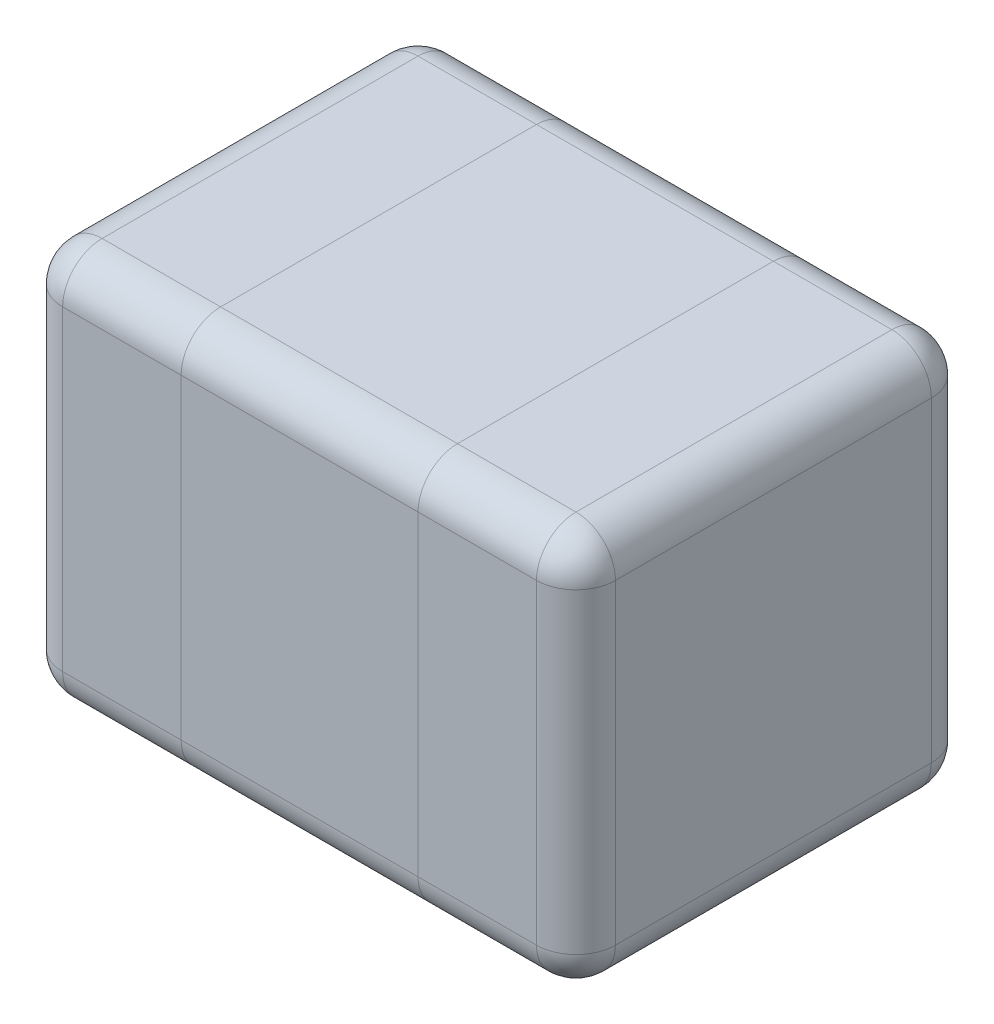
SolidWorks part; units mm, degrees
ref_plane "Alzado" through (0, 0, 0) normal (0, 0, 1) x (1, 0, 0)
ref_plane "Planta" through (0, 0, 0) normal (0, 1, 0) x (1, 0, 0)
ref_plane "Vista lateral" through (0, 0, 0) normal (1, 0, 0) x (0, 0, -1)
sketch "Croquis1" plane through (0, 0, 0) normal (0, 1, 0) x (1, 0, 0)
  line L1 (-0.15, -0.25) -> (0.15, -0.25)
  line L2 (-0.15, -0.25) -> (-0.15, 0.25)
  line L3 (-0.15, 0.25) -> (0.15, 0.25)
  line L4 (0.15, -0.25) -> (0.15, 0.25)
  line L5 (-0.15, -0.25) -> (0.15, 0.25) construction
  line L6 (-0.15, 0.25) -> (0.15, -0.25) construction
  point P0 (0, 0)
  dimension "D1" = 0.3
  dimension "D2" = 0.5
extrude "Saliente-Extruir1" add sketch "Croquis1" along normal blind 0.5
sketch "Croquis3" plane through (0, 0, 0) normal (0, 1, 0) x (1, 0, 0)
  line L0 (0.15, 0.25) -> (0.35, 0.25)
  line L1 (0.35, 0.25) -> (0.35, -0.25)
  line L2 (0.35, -0.25) -> (0.15, -0.25)
  line L3 (0.15, -0.25) -> (0.15, 0.25) construction
  line L4 (0.15, -0.25) -> (0.15, 0.25)
  line L5 (0, 1.3421) -> (0, -1.4057) construction
  line L6 (-0.15, -0.25) -> (-0.15, 0.25)
  line L7 (-0.35, -0.25) -> (-0.15, -0.25)
  line L8 (-0.35, 0.25) -> (-0.35, -0.25)
  line L9 (-0.15, 0.25) -> (-0.35, 0.25)
  dimension "D1" = 0.2
extrude "Saliente-Extruir3" add sketch "Croquis3" along normal blind 0.5 separate body
fillet "Redondeo2" radius 0.05 4 edges at (0, 0, 0.25) (0, 0.5, 0.25) (0, 0, -0.25) (0, 0.5, -0.25)
fillet "Redondeo4" radius 0.05 8 edges at (0.35, 0.25, 0.25) (0.35, 0.5, 0) (0.35, 0.25, -0.25) (0.35, 0, 0) (0.25, 0, 0.25) (0.25, 0.5, 0.25) (0.25, 0.5, -0.25) (0.25, 0, -0.25)
fillet "Redondeo5" radius 0.05 8 edges at (-0.35, 0.25, -0.25) (-0.35, 0.5, 0) (-0.35, 0.25, 0.25) (-0.35, 0, 0) (-0.25, 0, -0.25) (-0.25, 0.5, -0.25) (-0.25, 0, 0.25) (-0.25, 0.5, 0.25)
